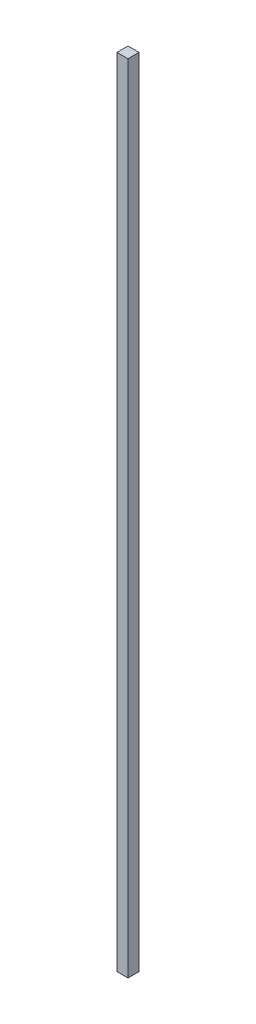
SolidWorks part; units mm, degrees
ref_plane "Front Plane" through (0, 0, 0) normal (0, 0, 1) x (1, 0, 0)
ref_plane "Top Plane" through (0, 0, 0) normal (0, 1, 0) x (1, 0, 0)
ref_plane "Right Plane" through (0, 0, 0) normal (1, 0, 0) x (0, 0, -1)
sketch "Sketch2" plane through (0, 0, 0) normal (0, 1, 0) x (1, 0, 0)
  line L1 (0, 0) -> (-25.4, 0)
  line L2 (0, 0) -> (0, -25.4)
  line L3 (0, -25.4) -> (-25.4, -25.4)
  line L4 (-25.4, 0) -> (-25.4, -25.4)
  dimension "D1" = 25.4
  dimension "D2" = 25.4
extrude "Boss-Extrude1" add sketch "Sketch2" along normal blind 1828.8
